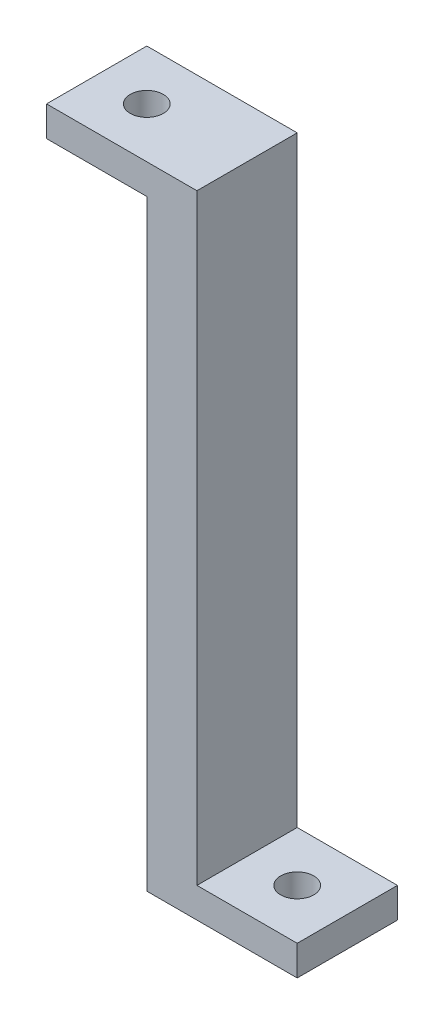
SolidWorks part; units mm, degrees
ref_plane "正面" through (0, 0, 0) normal (0, 0, 1) x (1, 0, 0)
ref_plane "平面" through (0, 0, 0) normal (0, 1, 0) x (1, 0, 0)
ref_plane "右側面" through (0, 0, 0) normal (1, 0, 0) x (0, 0, -1)
sketch "ｽｹｯﾁ1" plane through (0, 0, 0) normal (0, 0, 1) x (1, 0, 0)
  line L0 (0, 0) -> (-10, 0)
  line L1 (-10, 0) -> (-10, 3)
  line L2 (-10, 3) -> (5, 3)
  line L3 (5, 3) -> (5, -57)
  line L4 (5, -57) -> (15, -57)
  line L5 (15, -57) -> (15, -60)
  line L6 (15, -60) -> (0, -60)
  line L7 (0, -60) -> (0, 0)
  dimension "D1" = 3
  dimension "D2" = 3
  dimension "D3" = 5
  dimension "D4" = 60
  dimension "D5" = 10
  dimension "D6" = 10
extrude "ﾎﾞｽ - 押し出し1" add sketch "ｽｹｯﾁ1" along normal blind 10
sketch "ｽｹｯﾁ3" plane through (0, 3, 0) normal (0, 1, 0) x (1, 0, 0)
  line L0 (5, -5) -> (-10, -5) construction
  line L1 (5, -10) -> (5, 0) construction
  line L2 (-10, -10) -> (-10, 0) construction
  circle A0 centre (-5, -5) radius 1.65
  dimension "D1" = 3.3
  dimension "D2" = 5
extrude "ｶｯﾄ - 押し出し1" cut sketch "ｽｹｯﾁ3" against normal blind 10
sketch "ｽｹｯﾁ4" plane through (0, -57, 0) normal (0, 1, 0) x (1, 0, 0)
  line L0 (15, -5) -> (5, -5) construction
  line L1 (15, -10) -> (15, 0) construction
  line L2 (5, -10) -> (5, 0) construction
  circle A0 centre (10, -5) radius 1.65
  dimension "D2" = 3.3
  dimension "D1" = 5
extrude "ｶｯﾄ - 押し出し2" cut sketch "ｽｹｯﾁ4" against normal blind 10
sketch "ｽｹｯﾁ5" [suppressed] plane through (0, 3, 0) normal (0, 1, 0) x (1, 0, 0)
  circle A0 centre (-5, -5) radius 2.15
  dimension "D1" = 4.3
extrude "ｶｯﾄ - 押し出し3" [suppressed] cut sketch "ｽｹｯﾁ5" against normal blind 10
